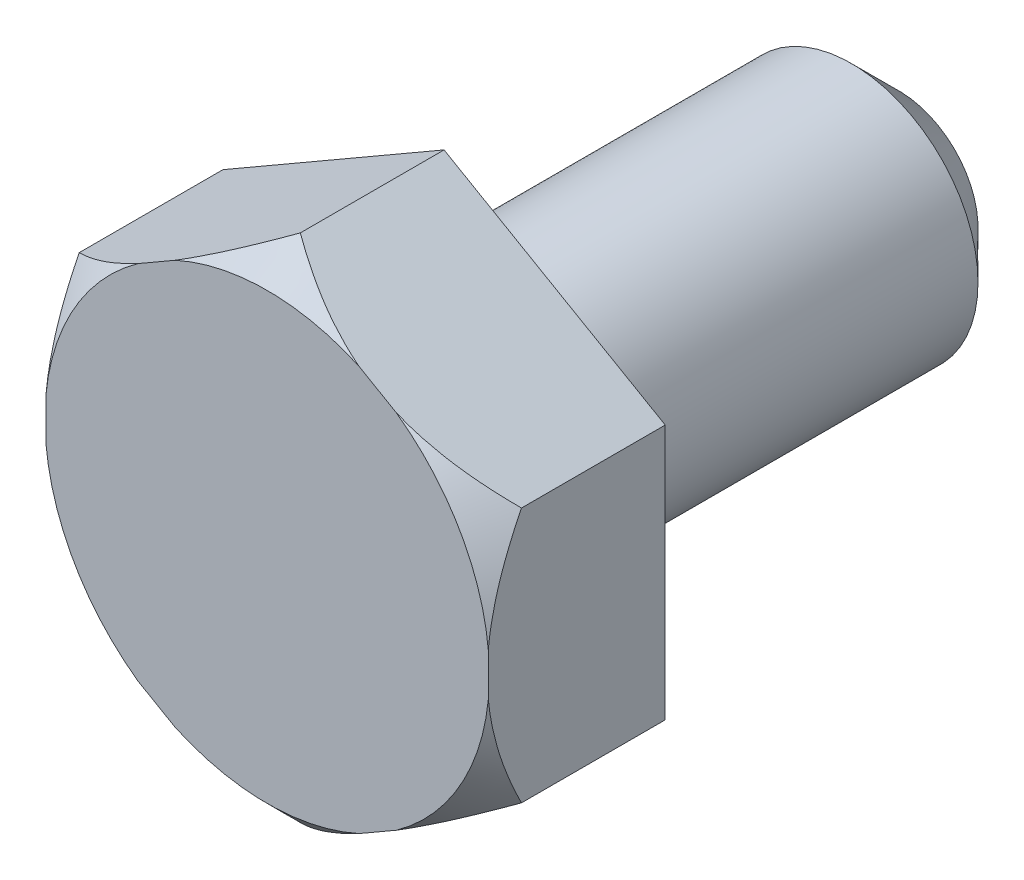
SolidWorks part; units mm, degrees
ref_plane "Спереди" through (0, 0, 0) normal (0, 0, 1) x (1, 0, 0)
ref_plane "Сверху" through (0, 0, 0) normal (0, 1, 0) x (1, 0, 0)
ref_plane "Справа" through (0, 0, 0) normal (1, 0, 0) x (0, 0, -1)
sketch "Эскиз1" plane through (0, 0, 0) normal (0, 0, 1) x (1, 0, 0)
  line L0 (0, 4.93) -> (0, -5.4719) construction
  line L1 (-5.0323, 0) -> (5.1026, 0) construction
  line L3 (0, 4.0415) -> (-3.5, 2.0207)
  line L4 (-3.5, 2.0207) -> (-3.5, -2.0207)
  line L5 (-3.5, -2.0207) -> (0, -4.0415)
  line L6 (0, -4.0415) -> (3.5, -2.0207)
  line L7 (3.5, -2.0207) -> (3.5, 2.0207)
  line L8 (3.5, 2.0207) -> (0, 4.0415)
  circle A0 centre (0, 0) radius 3.5 construction
extrude "Вытянуть1" add sketch "Эскиз1" along normal blind 2.8
sketch "Эскиз2" plane through (0, 0, 0) normal (0, 0, -1) x (-1, 0, 0)
  circle A0 centre (0, 0) radius 2
extrude "Вытянуть2" add sketch "Эскиз2" along normal blind 7.2
ref_axis "Ось4" through (0, 0, 5.2653) along (0, 0, -1)
sketch "Эскиз15" plane through (0, 0, 0) normal (1, 0, 0) x (0, 0, -1)
  line L0 (-2.8, 4.0415) -> (-2.8, 3.5165)
  line L1 (-2.8, 2.0207) -> (-2.8, 4.0415) construction
  line L2 (-2.8, 3.5165) -> (-2.275, 4.0415)
  line L3 (-2.8, 4.0415) -> (0, 4.0415) construction
  line L4 (-2.275, 4.0415) -> (-2.8, 4.0415)
revolve "Вырез-Повернуть1" cut sketch "Эскиз15" angle 360 about axis through (0, 0, 5.2653) along (0, 0, -1)
ref_plane "Плоскость1" through (3.5, 0.3398, 2.8) normal (-0.0966, 0.9953, 0) x (-0.9953, -0.0966, 0)
chamfer "Фаска1" distance 0.75 angle 45 1 edges at (-2, 0, -7.2)
